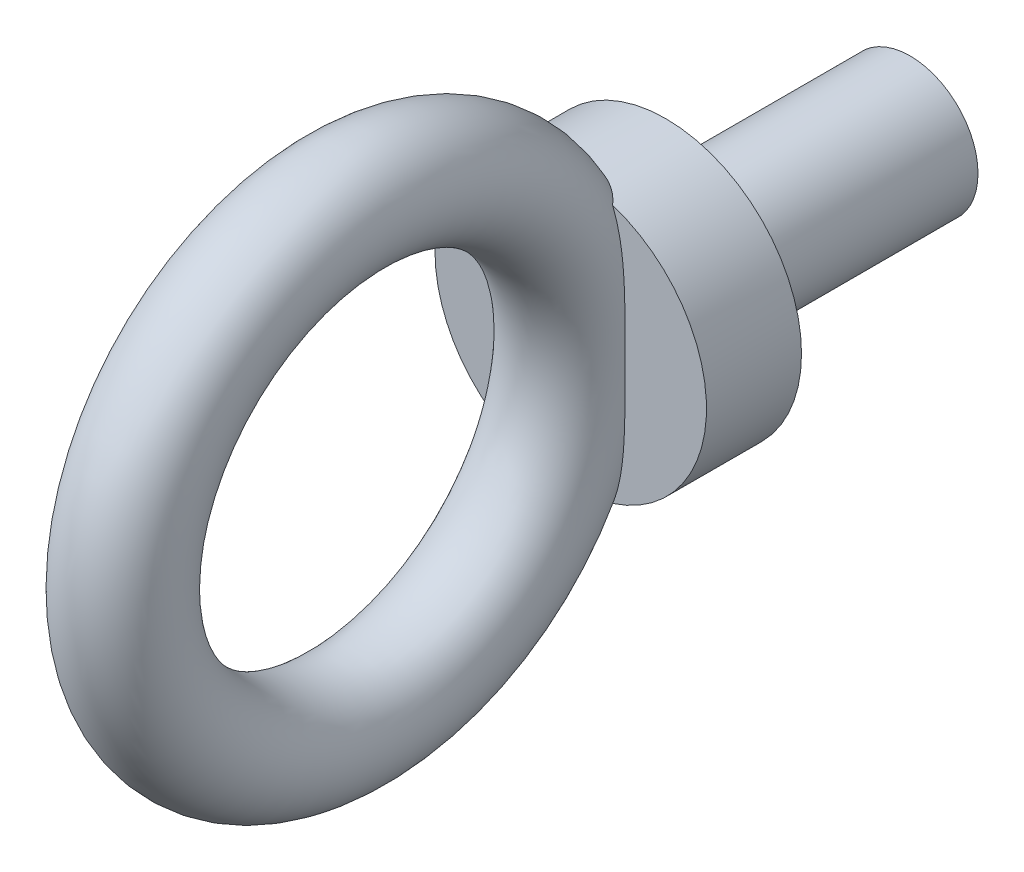
SolidWorks part; units mm, degrees
ref_plane "正面" through (0, 0, 0) normal (0, 0, 1) x (1, 0, 0)
ref_plane "平面" through (0, 0, 0) normal (0, 1, 0) x (1, 0, 0)
ref_plane "右側面" through (0, 0, 0) normal (1, 0, 0) x (0, 0, -1)
sketch "ｽｹｯﾁ1" plane through (0, 0, 0) normal (0, 0, 1) x (1, 0, 0)
  circle A0 centre (0, 0) radius 5
  dimension "D1" = 10
extrude "ﾎﾞｽ - 押し出し1" add sketch "ｽｹｯﾁ1" along normal blind 25
cosmetic thread "ねじ山1" parameters "D1"=15, "D2"=8.619
sketch "ｽｹｯﾁ2" plane through (0, 0, 0) normal (0, 1, 0) x (1, 0, 0)
  line L0 (-5, -25) -> (5, -25) construction
  line L1 (-5, -25) -> (5, -25)
  circle A0 centre (0, -25) radius 4
  dimension "D1" = 8
sketch "ｽｹｯﾁ3" plane through (0, 0, 0) normal (1, 0, 0) x (0, 0, -1)
  line L0 (-25, 5) -> (-25, -5) construction
  line L1 (-25, 5) -> (-25, -5)
  circle A0 centre (-41.5, 0) radius 16.5
  dimension "D1" = 33
sweep "ｽｲｰﾌﾟ1" add profiles "ｽｹｯﾁ2" path "ｽｹｯﾁ3"
ref_plane "平面1" through (0, 0, 18) normal (0, 0, -1) x (-1, 0, 0)
sketch "ｽｹｯﾁ4" plane through (0, 0, 18) normal (0, 0, -1) x (-1, 0, 0)
  circle A0 centre (0, 0) radius 10
  dimension "D1" = 20
extrude "ﾎﾞｽ - 押し出し2" add sketch "ｽｹｯﾁ4" against normal blind 7
sketch "ｽｹｯﾁ5" plane through (0, 0, 0) normal (1, 0, 0) x (0, 0, -1)
  arc A0 (-23.6045, 10) -> (-23.6045, -10) centre (-41.5, 0) ccw construction
  point P0 (-62, 0)
sketch "ｽｹｯﾁ6" plane through (0, 0, 0) normal (1, 0, 0) x (0, 0, -1)
  arc A0 (-23.6045, 10) -> (-23.6045, -10) centre (-41.5, 0) ccw construction
  point P0 (-41.5, 20.5)
  point P1 (-41.5, -20.5)
